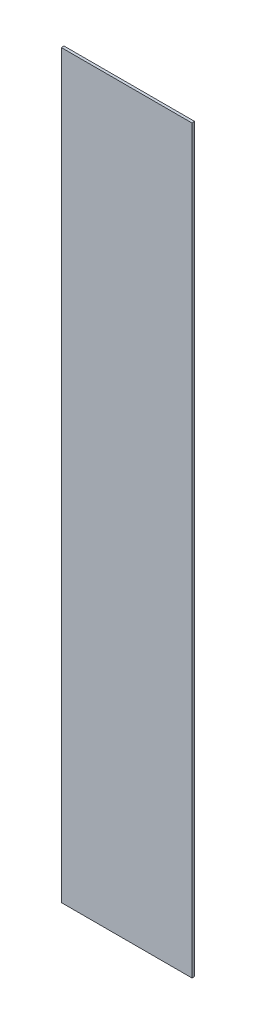
SolidWorks part; units mm, degrees
material "AISI 1045 Steel, cold drawn"
ref_plane "Front Plane" through (0, 0, 0) normal (0, 0, 1) x (1, 0, 0)
ref_plane "Top Plane" through (0, 0, 0) normal (0, 1, 0) x (1, 0, 0)
ref_plane "Right Plane" through (0, 0, 0) normal (1, 0, 0) x (0, 0, -1)
sketch "Sketch1" plane through (0, 0, 0) normal (0, 0, 1) x (1, 0, 0)
  line L1 (48.5, -275) -> (-48.5, -275)
  line L2 (48.5, -275) -> (48.5, 275)
  line L3 (48.5, 275) -> (-48.5, 275)
  line L4 (-48.5, -275) -> (-48.5, 275)
  line L5 (48.5, -275) -> (-48.5, 275) construction
  line L6 (48.5, 275) -> (-48.5, -275) construction
  point P0 (0, 0)
  dimension "D1" = 97
  dimension "D2" = 550
extrude "Boss-Extrude1" add sketch "Sketch1" along normal mid plane 2
